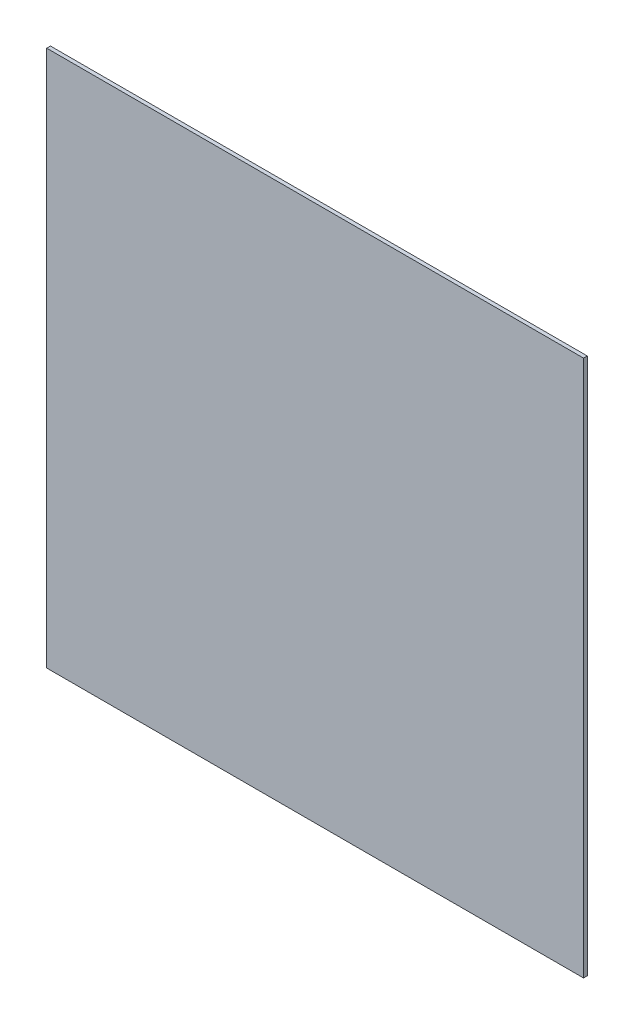
SolidWorks part; units mm, degrees
material "ABS PC"
ref_plane "Front Plane" through (0, 0, 0) normal (0, 0, 1) x (1, 0, 0)
ref_plane "Top Plane" through (0, 0, 0) normal (0, 1, 0) x (1, 0, 0)
ref_plane "Right Plane" through (0, 0, 0) normal (1, 0, 0) x (0, 0, -1)
sketch "Sketch1" plane through (0, 0, 0) normal (0, 0, 1) x (1, 0, 0)
  line L1 (-12.7, 12.7) -> (12.7, 12.7)
  line L2 (-12.7, 12.7) -> (-12.7, -12.7)
  line L3 (-12.7, -12.7) -> (12.7, -12.7)
  line L4 (12.7, 12.7) -> (12.7, -12.7)
  line L5 (-12.7, 12.7) -> (12.7, -12.7) construction
  line L6 (-12.7, -12.7) -> (12.7, 12.7) construction
  point P0 (0, 0)
  dimension "D1" = 25.4
extrude "Boss-Extrude1" add sketch "Sketch1" along normal blind 0.1778
